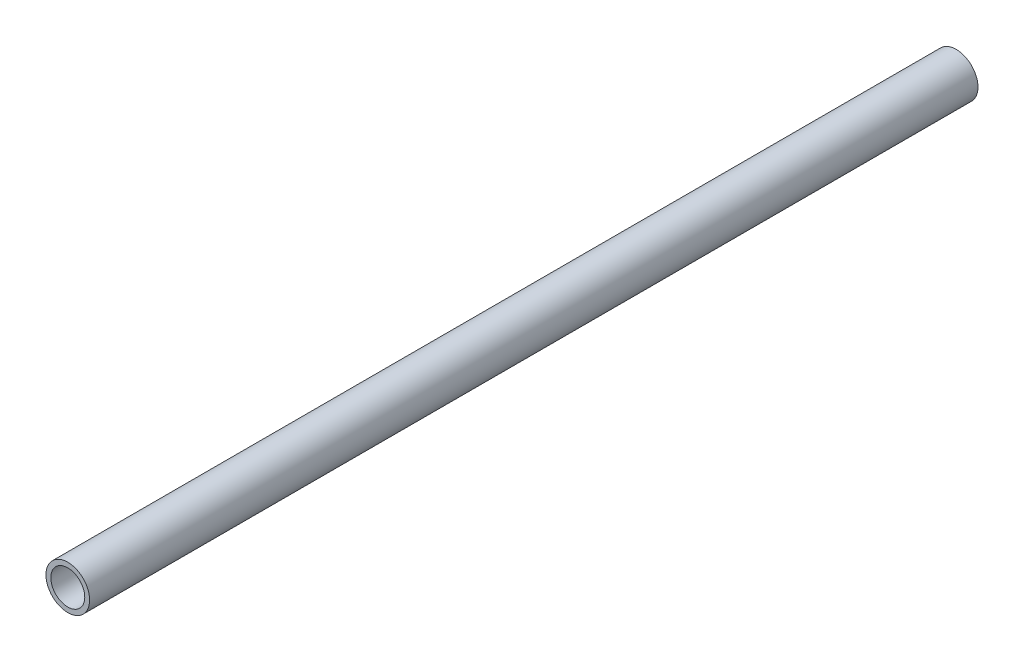
SolidWorks part; units mm, degrees
ref_plane "Front Plane" through (0, 0, 0) normal (0, 0, 1) x (1, 0, 0)
ref_plane "Top Plane" through (0, 0, 0) normal (0, 1, 0) x (1, 0, 0)
ref_plane "Right Plane" through (0, 0, 0) normal (1, 0, 0) x (0, 0, -1)
sketch "Sketch1" plane through (0, 0, 0) normal (0, 0, 1) x (1, 0, 0)
  circle A0 centre (0, 0) radius 9
  circle A1 centre (0, 0) radius 7
  dimension "D1" = 14
  dimension "D2" = 18
extrude "Boss-Extrude1" add sketch "Sketch1" along normal blind 366.3
